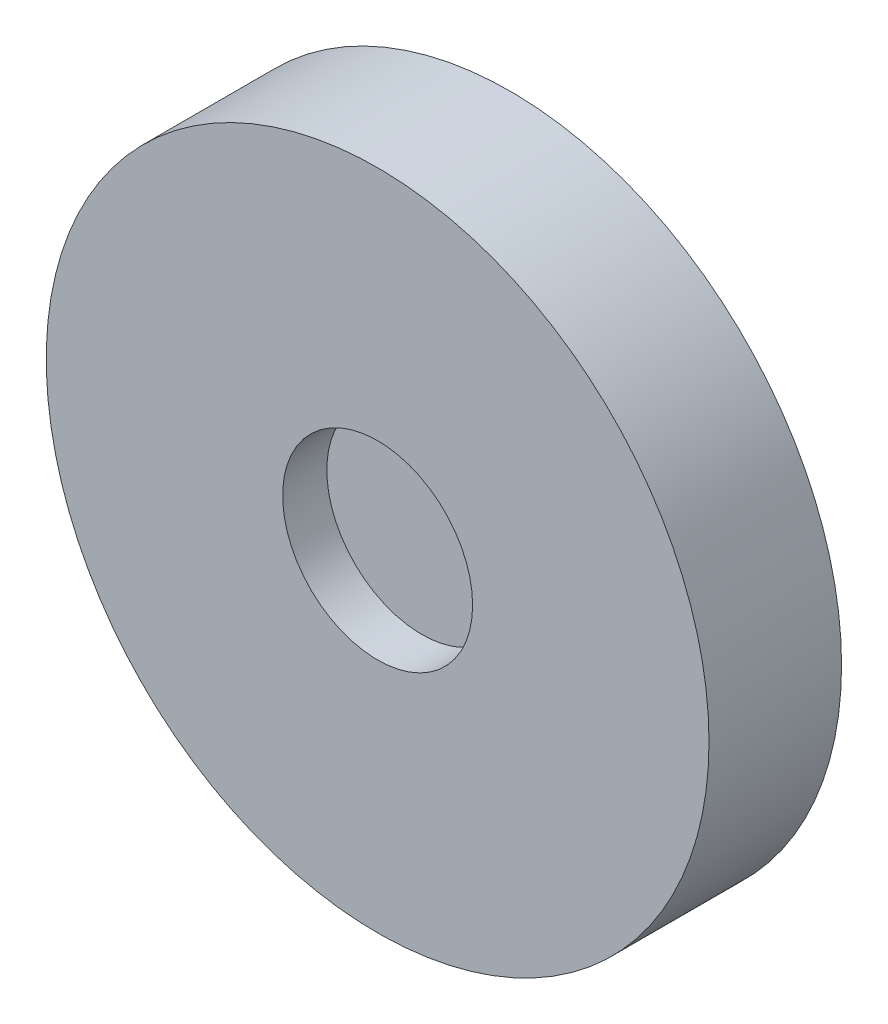
SolidWorks part; units mm, degrees
ref_plane "Front Plane" through (0, 0, 0) normal (0, 0, 1) x (1, 0, 0)
ref_plane "Top Plane" through (0, 0, 0) normal (0, 1, 0) x (1, 0, 0)
ref_plane "Right Plane" through (0, 0, 0) normal (1, 0, 0) x (0, 0, -1)
sketch "Sketch1" plane through (0, 0, 0) normal (0, 0, 1) x (1, 0, 0)
  circle A0 centre (0, 0) radius 7.5
  dimension "D1" = 15
extrude "Boss-Extrude1" add sketch "Sketch1" along normal blind 3
sketch "Sketch2" plane through (0, 0, 3) normal (0, 0, 1) x (1, 0, 0)
  circle A0 centre (0, 0) radius 2.15
  dimension "D1" = 4.3
extrude "Cut-Extrude1" cut sketch "Sketch2" against normal blind 1
